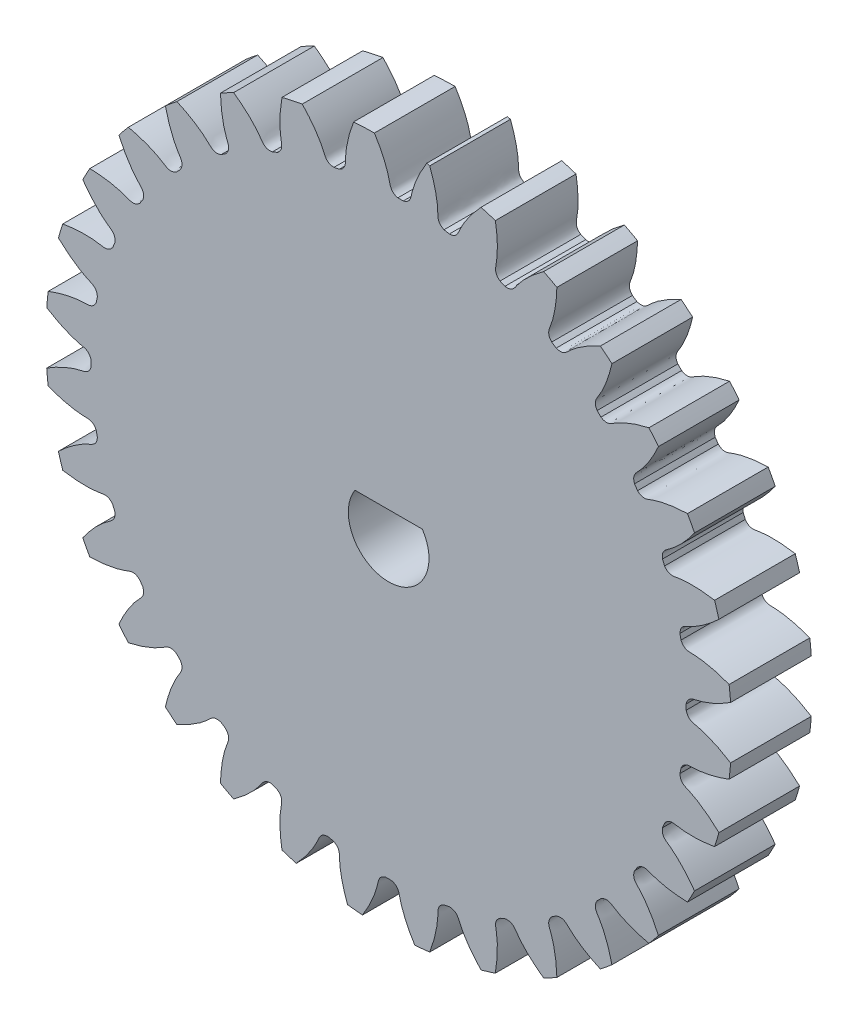
SolidWorks part; units mm, degrees
ref_plane "前视基准面" through (0, 0, 0) normal (0, 0, 1) x (1, 0, 0)
ref_plane "上视基准面" through (0, 0, 0) normal (0, 1, 0) x (1, 0, 0)
ref_plane "右视基准面" through (0, 0, 0) normal (1, 0, 0) x (0, 0, -1)
sketch "草图1" plane through (0, 0, 0) normal (0, 0, 1) x (1, 0, 0)
  line L1 (-1.6703, 1.1) -> (1.6703, 1.1)
  arc A0 (2.0353, 16.8777) -> (1.887, 16.9176) centre (-2.4495, 0.5141) ccw
  arc A1 (0.7245, 14.7165) -> (0.4565, 14.7165) centre (0.5905, -0.0328) ccw
  arc A2 (-0.706, 16.9176) -> (-1.7388, 16.8777) centre (-0.5662, -0.0818) ccw
  arc A3 (-2.4495, 14.4921) -> (-2.7124, 14.4398) centre (0.2965, 0) ccw
  arc A4 (-4.282, 16.3719) -> (-5.2889, 16.1564) centre (-1.2293, -0.3518) ccw
  arc A5 (-5.5205, 13.678) -> (-5.7682, 13.5754) centre (0, 0) ccw
  arc A6 (-7.6845, 15.1641) -> (-8.3392, 14.8141) centre (0, 0) ccw
  arc A7 (-8.0829, 12.3381) -> (-8.3058, 12.1892) centre (0, 0) ccw
  arc A8 (-10.4952, 13.3735) -> (-11.069, 12.9026) centre (0, 0) ccw
  arc A9 (-10.3346, 10.5242) -> (-10.5242, 10.3346) centre (0, 0) ccw
  arc A10 (-12.9026, 11.069) -> (-13.3735, 10.4952) centre (0, 0) ccw
  arc A11 (-12.1892, 8.3058) -> (-12.3381, 8.0829) centre (0, 0) ccw
  arc A12 (-14.8141, 8.3392) -> (-15.1641, 7.6845) centre (0, 0) ccw
  arc A13 (-13.5754, 5.7682) -> (-13.678, 5.5205) centre (0, 0) ccw
  arc A14 (-16.1564, 5.2889) -> (-16.3719, 4.5785) centre (0, 0) ccw
  arc A15 (-14.4398, 3.0089) -> (-14.4921, 2.746) centre (0, 0) ccw
  arc A16 (-16.8777, 2.0353) -> (-16.9505, 1.2965) centre (0, 0) ccw
  arc A17 (-14.7494, 0.134) -> (-14.7494, -0.134) centre (0, 0) ccw
  arc A18 (-16.9505, -1.2965) -> (-16.8777, -2.0353) centre (0, 0) ccw
  arc A19 (-14.4921, -2.746) -> (-14.4398, -3.0089) centre (0, 0) ccw
  arc A20 (-16.3719, -4.5785) -> (-16.1564, -5.2889) centre (0, 0) ccw
  arc A21 (-13.678, -5.5205) -> (-13.5754, -5.7682) centre (0, 0) ccw
  arc A22 (-15.1641, -7.6845) -> (-14.8141, -8.3392) centre (0, 0) ccw
  arc A23 (-12.3381, -8.0829) -> (-12.1892, -8.3058) centre (0, 0) ccw
  arc A24 (-13.3735, -10.4952) -> (-12.9026, -11.069) centre (0, 0) ccw
  arc A25 (-10.5242, -10.3346) -> (-10.3346, -10.5242) centre (0, 0) ccw
  arc A26 (-11.069, -12.9026) -> (-10.4952, -13.3735) centre (0, 0) ccw
  arc A27 (-8.3058, -12.1892) -> (-8.0829, -12.3381) centre (0, 0) ccw
  arc A28 (-8.3392, -14.8141) -> (-7.6845, -15.1641) centre (0, 0) ccw
  arc A29 (-5.7682, -13.5754) -> (-5.5205, -13.678) centre (0, 0) ccw
  arc A30 (-5.2889, -16.1564) -> (-4.5785, -16.3719) centre (0, 0) ccw
  arc A31 (-3.0089, -14.4398) -> (-2.746, -14.4921) centre (0, 0) ccw
  arc A32 (-2.0353, -16.8777) -> (-1.2965, -16.9505) centre (0, 0) ccw
  arc A33 (-0.134, -14.7494) -> (0.134, -14.7494) centre (0, 0) ccw
  arc A34 (1.2965, -16.9505) -> (2.0353, -16.8777) centre (0, 0) ccw
  arc A35 (2.746, -14.4921) -> (3.0089, -14.4398) centre (0, 0) ccw
  arc A36 (4.5785, -16.3719) -> (5.2889, -16.1564) centre (0, 0) ccw
  arc A37 (5.5205, -13.678) -> (5.7682, -13.5754) centre (0, 0) ccw
  arc A38 (7.6845, -15.1641) -> (8.3392, -14.8141) centre (0, 0) ccw
  arc A39 (8.0829, -12.3381) -> (8.3058, -12.1892) centre (0, 0) ccw
  arc A40 (10.4952, -13.3735) -> (11.069, -12.9026) centre (0, 0) ccw
  arc A41 (10.3346, -10.5242) -> (10.5242, -10.3346) centre (0, 0) ccw
  arc A42 (12.9026, -11.069) -> (13.3735, -10.4952) centre (0, 0) ccw
  arc A43 (12.1892, -8.3058) -> (12.3381, -8.0829) centre (0, 0) ccw
  arc A44 (14.8141, -8.3392) -> (15.1641, -7.6845) centre (0, 0) ccw
  arc A45 (13.5754, -5.7682) -> (13.678, -5.5205) centre (0, 0) ccw
  arc A46 (16.1564, -5.2889) -> (16.3719, -4.5785) centre (0, 0) ccw
  arc A47 (14.4398, -3.0089) -> (14.4921, -2.746) centre (0, 0) ccw
  arc A48 (16.8777, -2.0353) -> (16.9505, -1.2965) centre (0, 0) ccw
  arc A49 (14.7494, -0.134) -> (14.7494, 0.134) centre (0, 0) ccw
  arc A50 (16.9505, 1.2965) -> (16.8777, 2.0353) centre (0, 0) ccw
  arc A51 (14.4921, 2.746) -> (14.4398, 3.0089) centre (0, 0) ccw
  arc A52 (16.3719, 4.5785) -> (16.1564, 5.2889) centre (0, 0) ccw
  arc A53 (13.678, 5.5205) -> (13.5754, 5.7682) centre (0, 0) ccw
  arc A54 (15.1641, 7.6845) -> (14.8141, 8.3392) centre (0, 0) ccw
  arc A55 (12.3381, 8.0829) -> (12.1892, 8.3058) centre (0, 0) ccw
  arc A56 (13.3735, 10.4952) -> (12.9026, 11.069) centre (0, 0) ccw
  arc A57 (10.5242, 10.3346) -> (10.3346, 10.5242) centre (0, 0) ccw
  arc A58 (11.069, 12.9026) -> (10.4952, 13.3735) centre (0, 0) ccw
  arc A59 (8.3058, 12.1892) -> (8.0829, 12.3381) centre (0, 0) ccw
  arc A60 (8.3392, 14.8141) -> (7.6845, 15.1641) centre (0, 0) ccw
  arc A61 (5.7682, 13.5754) -> (5.5205, 13.678) centre (0, 0) ccw
  arc A62 (5.2889, 16.1564) -> (4.5785, 16.3719) centre (0, 0) ccw
  arc A63 (3.0089, 14.4398) -> (2.746, 14.4921) centre (0, 0) ccw
  arc A65 (-1.6703, 1.1) -> (1.6703, 1.1) centre (0, 0) ccw
  spline S0 degree 3 poles (1.887, 16.9176) (1.8385, 16.8406) (1.7423, 16.6818) (1.61, 16.4438) (1.493, 16.2117) (1.3953, 15.9971) (1.3153, 15.801) (1.2513, 15.6245) (1.2085, 15.4897) (1.1809, 15.3925) (1.1639, 15.3279) (1.0989, 15.0596) (1.0793, 14.8023) (0.7245, 14.7165) knots 0 0 0 0 0.048515 0.098957 0.145126 0.18702 0.22464 0.257986 0.287058 0.299991 0.311856 0.322652 0.447185 0.447185 0.447185 0.447185
  spline S1 degree 3 poles (0.4565, 14.7165) (0.1017, 14.8023) (0.0821, 15.0596) (0.0171, 15.3279) (0.0001, 15.3925) (-0.0275, 15.4897) (-0.0703, 15.6245) (-0.1342, 15.801) (-0.2142, 15.9971) (-0.312, 16.2117) (-0.429, 16.4438) (-0.5613, 16.6818) (-0.6575, 16.8406) (-0.706, 16.9176) knots 0 0 0 0 0.124533 0.135329 0.147193 0.160126 0.189198 0.222544 0.260164 0.302059 0.348227 0.39867 0.447185 0.447185 0.447185 0.447185
  spline S2 degree 3 poles (-1.7388, 16.8777) (-1.7713, 16.7927) (-1.8347, 16.6182) (-1.918, 16.3589) (-1.9875, 16.1085) (-2.0415, 15.8789) (-2.0817, 15.671) (-2.11, 15.4854) (-2.1257, 15.3449) (-2.1338, 15.2441) (-2.1378, 15.1775) (-2.1493, 14.9016) (-2.1183, 14.6455) (-2.4495, 14.4921) knots 0 0 0 0 0.048515 0.098957 0.145126 0.18702 0.22464 0.257986 0.287058 0.299991 0.311856 0.322652 0.447185 0.447185 0.447185 0.447185
  spline S3 degree 3 poles (-2.7124, 14.4398) (-3.0771, 14.4548) (-3.1465, 14.7032) (-3.2626, 14.9537) (-3.2919, 15.0138) (-3.3379, 15.1038) (-3.4062, 15.2276) (-3.5033, 15.3882) (-3.6201, 15.5649) (-3.7578, 15.7564) (-3.9179, 15.9611) (-4.094, 16.1688) (-4.2194, 16.3058) (-4.282, 16.3719) knots 0 0 0 0 0.124533 0.135329 0.147193 0.160126 0.189198 0.222544 0.260164 0.302059 0.348227 0.39867 0.447185 0.447185 0.447185 0.447185
  spline S4 degree 3 poles (-5.2889, 16.1564) (-5.3042, 16.0666) (-5.3323, 15.8831) (-5.3634, 15.6126) (-5.3827, 15.3534) (-5.3909, 15.1177) (-5.3898, 14.9059) (-5.3813, 14.7184) (-5.3693, 14.5775) (-5.3576, 14.4771) (-5.3485, 14.4109) (-5.3059, 14.1381) (-5.2256, 13.893) (-5.5205, 13.678) knots 0 0 0 0 0.048515 0.098957 0.145126 0.18702 0.22464 0.257986 0.287058 0.299991 0.311856 0.322652 0.447185 0.447185 0.447185 0.447185
  spline S5 degree 3 poles (-5.7682, 13.5754) (-6.1288, 13.5188) (-6.2453, 13.749) (-6.4081, 13.9721) (-6.4485, 14.0253) (-6.5112, 14.1045) (-6.6023, 14.2126) (-6.7289, 14.3512) (-6.8779, 14.5017) (-7.0503, 14.6626) (-7.2473, 14.8322) (-7.4605, 15.0016) (-7.6102, 15.1115) (-7.6845, 15.1641) knots 0 0 0 0 0.124533 0.135329 0.147193 0.160126 0.189198 0.222544 0.260164 0.302059 0.348227 0.39867 0.447185 0.447185 0.447185 0.447185
  spline S6 degree 3 poles (-8.3392, 14.8141) (-8.3367, 14.7231) (-8.3285, 14.5376) (-8.3062, 14.2662) (-8.2746, 14.0082) (-8.2366, 13.7755) (-8.1942, 13.568) (-8.1493, 13.3857) (-8.1101, 13.2499) (-8.079, 13.1537) (-8.0572, 13.0906) (-7.9622, 12.8313) (-7.8355, 12.6066) (-8.0829, 12.3381) knots 0 0 0 0 0.048515 0.098957 0.145126 0.18702 0.22464 0.257986 0.287058 0.299991 0.311856 0.322652 0.447185 0.447185 0.447185 0.447185
  spline S7 degree 3 poles (-8.3058, 12.1892) (-8.6484, 12.0634) (-8.8076, 12.2664) (-9.0108, 12.4534) (-9.0607, 12.4977) (-9.1377, 12.5632) (-9.2482, 12.6515) (-9.3994, 12.7627) (-9.5749, 12.8813) (-9.7754, 13.0055) (-10.0016, 13.1334) (-10.2439, 13.2578) (-10.4121, 13.3364) (-10.4952, 13.3735) knots 0 0 0 0 0.124533 0.135329 0.147193 0.160126 0.189198 0.222544 0.260164 0.302059 0.348227 0.39867 0.447185 0.447185 0.447185 0.447185
  spline S8 degree 3 poles (-11.069, 12.9026) (-11.0489, 12.8138) (-11.0046, 12.6335) (-10.9298, 12.3716) (-10.8485, 12.1248) (-10.7658, 11.9039) (-10.6837, 11.7087) (-10.6041, 11.5387) (-10.5391, 11.4131) (-10.4899, 11.3248) (-10.4562, 11.2672) (-10.3125, 11.0314) (-10.1444, 10.8357) (-10.3346, 10.5242) knots 0 0 0 0 0.048515 0.098957 0.145126 0.18702 0.22464 0.257986 0.287058 0.299991 0.311856 0.322652 0.447185 0.447185 0.447185 0.447185
  spline S9 degree 3 poles (-10.5242, 10.3346) (-10.8357, 10.1444) (-11.0314, 10.3125) (-11.2672, 10.4562) (-11.3248, 10.4899) (-11.4131, 10.5391) (-11.5387, 10.6041) (-11.7087, 10.6837) (-11.9039, 10.7658) (-12.1248, 10.8485) (-12.3716, 10.9298) (-12.6335, 11.0046) (-12.8138, 11.0489) (-12.9026, 11.069) knots 0 0 0 0 0.124533 0.135329 0.147193 0.160126 0.189198 0.222544 0.260164 0.302059 0.348227 0.39867 0.447185 0.447185 0.447185 0.447185
  spline S10 degree 3 poles (-13.3735, 10.4952) (-13.3364, 10.4121) (-13.2578, 10.2439) (-13.1334, 10.0016) (-13.0055, 9.7754) (-12.8813, 9.5749) (-12.7627, 9.3994) (-12.6515, 9.2482) (-12.5632, 9.1377) (-12.4977, 9.0607) (-12.4534, 9.0108) (-12.2664, 8.8076) (-12.0634, 8.6484) (-12.1892, 8.3058) knots 0 0 0 0 0.048515 0.098957 0.145126 0.18702 0.22464 0.257986 0.287058 0.299991 0.311856 0.322652 0.447185 0.447185 0.447185 0.447185
  spline S11 degree 3 poles (-12.3381, 8.0829) (-12.6066, 7.8355) (-12.8313, 7.9622) (-13.0906, 8.0572) (-13.1537, 8.079) (-13.2499, 8.1101) (-13.3857, 8.1493) (-13.568, 8.1942) (-13.7755, 8.2366) (-14.0082, 8.2746) (-14.2662, 8.3062) (-14.5376, 8.3285) (-14.7231, 8.3367) (-14.8141, 8.3392) knots 0 0 0 0 0.124533 0.135329 0.147193 0.160126 0.189198 0.222544 0.260164 0.302059 0.348227 0.39867 0.447185 0.447185 0.447185 0.447185
  spline S12 degree 3 poles (-15.1641, 7.6845) (-15.1115, 7.6102) (-15.0016, 7.4605) (-14.8322, 7.2473) (-14.6626, 7.0503) (-14.5017, 6.8779) (-14.3512, 6.7289) (-14.2126, 6.6023) (-14.1045, 6.5112) (-14.0253, 6.4485) (-13.9721, 6.4081) (-13.749, 6.2453) (-13.5188, 6.1288) (-13.5754, 5.7682) knots 0 0 0 0 0.048515 0.098957 0.145126 0.18702 0.22464 0.257986 0.287058 0.299991 0.311856 0.322652 0.447185 0.447185 0.447185 0.447185
  spline S13 degree 3 poles (-13.678, 5.5205) (-13.893, 5.2256) (-14.1381, 5.3059) (-14.4109, 5.3485) (-14.4771, 5.3576) (-14.5775, 5.3693) (-14.7184, 5.3813) (-14.9059, 5.3898) (-15.1177, 5.3909) (-15.3534, 5.3827) (-15.6126, 5.3634) (-15.8831, 5.3323) (-16.0666, 5.3042) (-16.1564, 5.2889) knots 0 0 0 0 0.124533 0.135329 0.147193 0.160126 0.189198 0.222544 0.260164 0.302059 0.348227 0.39867 0.447185 0.447185 0.447185 0.447185
  spline S14 degree 3 poles (-16.3719, 4.5785) (-16.3058, 4.5159) (-16.1688, 4.3905) (-15.9611, 4.2144) (-15.7564, 4.0543) (-15.5649, 3.9166) (-15.3882, 3.7998) (-15.2276, 3.7027) (-15.1038, 3.6344) (-15.0138, 3.5884) (-14.9537, 3.5591) (-14.7032, 3.443) (-14.4548, 3.3736) (-14.4398, 3.0089) knots 0 0 0 0 0.048515 0.098957 0.145126 0.18702 0.22464 0.257986 0.287058 0.299991 0.311856 0.322652 0.447185 0.447185 0.447185 0.447185
  spline S15 degree 3 poles (-14.4921, 2.746) (-14.6455, 2.4148) (-14.9016, 2.4458) (-15.1775, 2.4343) (-15.2441, 2.4303) (-15.3449, 2.4222) (-15.4854, 2.4065) (-15.671, 2.3782) (-15.8789, 2.338) (-16.1085, 2.284) (-16.3589, 2.2145) (-16.6182, 2.1312) (-16.7927, 2.0678) (-16.8777, 2.0353) knots 0 0 0 0 0.124533 0.135329 0.147193 0.160126 0.189198 0.222544 0.260164 0.302059 0.348227 0.39867 0.447185 0.447185 0.447185 0.447185
  spline S16 degree 3 poles (-16.9505, 1.2965) (-16.8735, 1.248) (-16.7147, 1.1518) (-16.4766, 1.0195) (-16.2446, 0.9025) (-16.0299, 0.8048) (-15.8338, 0.7247) (-15.6573, 0.6608) (-15.5226, 0.618) (-15.4254, 0.5904) (-15.3608, 0.5734) (-15.0924, 0.5084) (-14.8352, 0.4888) (-14.7494, 0.134) knots 0 0 0 0 0.048515 0.098957 0.145126 0.18702 0.22464 0.257986 0.287058 0.299991 0.311856 0.322652 0.447185 0.447185 0.447185 0.447185
  spline S17 degree 3 poles (-14.7494, -0.134) (-14.8352, -0.4888) (-15.0924, -0.5084) (-15.3608, -0.5734) (-15.4254, -0.5904) (-15.5226, -0.618) (-15.6573, -0.6608) (-15.8338, -0.7247) (-16.0299, -0.8048) (-16.2446, -0.9025) (-16.4766, -1.0195) (-16.7147, -1.1518) (-16.8735, -1.248) (-16.9505, -1.2965) knots 0 0 0 0 0.124533 0.135329 0.147193 0.160126 0.189198 0.222544 0.260164 0.302059 0.348227 0.39867 0.447185 0.447185 0.447185 0.447185
  spline S18 degree 3 poles (-16.8777, -2.0353) (-16.7927, -2.0678) (-16.6182, -2.1312) (-16.3589, -2.2145) (-16.1085, -2.284) (-15.8789, -2.338) (-15.671, -2.3782) (-15.4854, -2.4065) (-15.3449, -2.4222) (-15.2441, -2.4303) (-15.1775, -2.4343) (-14.9016, -2.4458) (-14.6455, -2.4148) (-14.4921, -2.746) knots 0 0 0 0 0.048515 0.098957 0.145126 0.18702 0.22464 0.257986 0.287058 0.299991 0.311856 0.322652 0.447185 0.447185 0.447185 0.447185
  spline S19 degree 3 poles (-14.4398, -3.0089) (-14.4548, -3.3736) (-14.7032, -3.443) (-14.9537, -3.5591) (-15.0138, -3.5884) (-15.1038, -3.6344) (-15.2276, -3.7027) (-15.3882, -3.7998) (-15.5649, -3.9166) (-15.7564, -4.0543) (-15.9611, -4.2144) (-16.1688, -4.3905) (-16.3058, -4.5159) (-16.3719, -4.5785) knots 0 0 0 0 0.124533 0.135329 0.147193 0.160126 0.189198 0.222544 0.260164 0.302059 0.348227 0.39867 0.447185 0.447185 0.447185 0.447185
  spline S20 degree 3 poles (-16.1564, -5.2889) (-16.0666, -5.3042) (-15.8831, -5.3323) (-15.6126, -5.3634) (-15.3534, -5.3827) (-15.1177, -5.3909) (-14.9059, -5.3898) (-14.7184, -5.3813) (-14.5775, -5.3693) (-14.4771, -5.3576) (-14.4109, -5.3485) (-14.1381, -5.3059) (-13.893, -5.2256) (-13.678, -5.5205) knots 0 0 0 0 0.048515 0.098957 0.145126 0.18702 0.22464 0.257986 0.287058 0.299991 0.311856 0.322652 0.447185 0.447185 0.447185 0.447185
  spline S21 degree 3 poles (-13.5754, -5.7682) (-13.5188, -6.1288) (-13.749, -6.2453) (-13.9721, -6.4081) (-14.0253, -6.4485) (-14.1045, -6.5112) (-14.2126, -6.6023) (-14.3512, -6.7289) (-14.5017, -6.8779) (-14.6626, -7.0503) (-14.8322, -7.2473) (-15.0016, -7.4605) (-15.1115, -7.6102) (-15.1641, -7.6845) knots 0 0 0 0 0.124533 0.135329 0.147193 0.160126 0.189198 0.222544 0.260164 0.302059 0.348227 0.39867 0.447185 0.447185 0.447185 0.447185
  spline S22 degree 3 poles (-14.8141, -8.3392) (-14.7231, -8.3367) (-14.5376, -8.3285) (-14.2662, -8.3062) (-14.0082, -8.2746) (-13.7755, -8.2366) (-13.568, -8.1942) (-13.3857, -8.1493) (-13.2499, -8.1101) (-13.1537, -8.079) (-13.0906, -8.0572) (-12.8313, -7.9622) (-12.6066, -7.8355) (-12.3381, -8.0829) knots 0 0 0 0 0.048515 0.098957 0.145126 0.18702 0.22464 0.257986 0.287058 0.299991 0.311856 0.322652 0.447185 0.447185 0.447185 0.447185
  spline S23 degree 3 poles (-12.1892, -8.3058) (-12.0634, -8.6484) (-12.2664, -8.8076) (-12.4534, -9.0108) (-12.4977, -9.0607) (-12.5632, -9.1377) (-12.6515, -9.2482) (-12.7627, -9.3994) (-12.8813, -9.5749) (-13.0055, -9.7754) (-13.1334, -10.0016) (-13.2578, -10.2439) (-13.3364, -10.4121) (-13.3735, -10.4952) knots 0 0 0 0 0.124533 0.135329 0.147193 0.160126 0.189198 0.222544 0.260164 0.302059 0.348227 0.39867 0.447185 0.447185 0.447185 0.447185
  spline S24 degree 3 poles (-12.9026, -11.069) (-12.8138, -11.0489) (-12.6335, -11.0046) (-12.3716, -10.9298) (-12.1248, -10.8485) (-11.9039, -10.7658) (-11.7087, -10.6837) (-11.5387, -10.6041) (-11.4131, -10.5391) (-11.3248, -10.4899) (-11.2672, -10.4562) (-11.0314, -10.3125) (-10.8357, -10.1444) (-10.5242, -10.3346) knots 0 0 0 0 0.048515 0.098957 0.145126 0.18702 0.22464 0.257986 0.287058 0.299991 0.311856 0.322652 0.447185 0.447185 0.447185 0.447185
  spline S25 degree 3 poles (-10.3346, -10.5242) (-10.1444, -10.8357) (-10.3125, -11.0314) (-10.4562, -11.2672) (-10.4899, -11.3248) (-10.5391, -11.4131) (-10.6041, -11.5387) (-10.6837, -11.7087) (-10.7658, -11.9039) (-10.8485, -12.1248) (-10.9298, -12.3716) (-11.0046, -12.6335) (-11.0489, -12.8138) (-11.069, -12.9026) knots 0 0 0 0 0.124533 0.135329 0.147193 0.160126 0.189198 0.222544 0.260164 0.302059 0.348227 0.39867 0.447185 0.447185 0.447185 0.447185
  spline S26 degree 3 poles (-10.4952, -13.3735) (-10.4121, -13.3364) (-10.2439, -13.2578) (-10.0016, -13.1334) (-9.7754, -13.0055) (-9.5749, -12.8813) (-9.3994, -12.7627) (-9.2482, -12.6515) (-9.1377, -12.5632) (-9.0607, -12.4977) (-9.0108, -12.4534) (-8.8076, -12.2664) (-8.6484, -12.0634) (-8.3058, -12.1892) knots 0 0 0 0 0.048515 0.098957 0.145126 0.18702 0.22464 0.257986 0.287058 0.299991 0.311856 0.322652 0.447185 0.447185 0.447185 0.447185
  spline S27 degree 3 poles (-8.0829, -12.3381) (-7.8355, -12.6066) (-7.9622, -12.8313) (-8.0572, -13.0906) (-8.079, -13.1537) (-8.1101, -13.2499) (-8.1493, -13.3857) (-8.1942, -13.568) (-8.2366, -13.7755) (-8.2746, -14.0082) (-8.3062, -14.2662) (-8.3285, -14.5376) (-8.3367, -14.7231) (-8.3392, -14.8141) knots 0 0 0 0 0.124533 0.135329 0.147193 0.160126 0.189198 0.222544 0.260164 0.302059 0.348227 0.39867 0.447185 0.447185 0.447185 0.447185
  spline S28 degree 3 poles (-7.6845, -15.1641) (-7.6102, -15.1115) (-7.4605, -15.0016) (-7.2473, -14.8322) (-7.0503, -14.6626) (-6.8779, -14.5017) (-6.7289, -14.3512) (-6.6023, -14.2126) (-6.5112, -14.1045) (-6.4485, -14.0253) (-6.4081, -13.9721) (-6.2453, -13.749) (-6.1288, -13.5188) (-5.7682, -13.5754) knots 0 0 0 0 0.048515 0.098957 0.145126 0.18702 0.22464 0.257986 0.287058 0.299991 0.311856 0.322652 0.447185 0.447185 0.447185 0.447185
  spline S29 degree 3 poles (-5.5205, -13.678) (-5.2256, -13.893) (-5.3059, -14.1381) (-5.3485, -14.4109) (-5.3576, -14.4771) (-5.3693, -14.5775) (-5.3813, -14.7184) (-5.3898, -14.9059) (-5.3909, -15.1177) (-5.3827, -15.3534) (-5.3634, -15.6126) (-5.3323, -15.8831) (-5.3042, -16.0666) (-5.2889, -16.1564) knots 0 0 0 0 0.124533 0.135329 0.147193 0.160126 0.189198 0.222544 0.260164 0.302059 0.348227 0.39867 0.447185 0.447185 0.447185 0.447185
  spline S30 degree 3 poles (-4.5785, -16.3719) (-4.5159, -16.3058) (-4.3905, -16.1688) (-4.2144, -15.9611) (-4.0543, -15.7564) (-3.9166, -15.5649) (-3.7998, -15.3882) (-3.7027, -15.2276) (-3.6344, -15.1038) (-3.5884, -15.0138) (-3.5591, -14.9537) (-3.443, -14.7032) (-3.3736, -14.4548) (-3.0089, -14.4398) knots 0 0 0 0 0.048515 0.098957 0.145126 0.18702 0.22464 0.257986 0.287058 0.299991 0.311856 0.322652 0.447185 0.447185 0.447185 0.447185
  spline S31 degree 3 poles (-2.746, -14.4921) (-2.4148, -14.6455) (-2.4458, -14.9016) (-2.4343, -15.1775) (-2.4303, -15.2441) (-2.4222, -15.3449) (-2.4065, -15.4854) (-2.3782, -15.671) (-2.338, -15.8789) (-2.284, -16.1085) (-2.2145, -16.3589) (-2.1312, -16.6182) (-2.0678, -16.7927) (-2.0353, -16.8777) knots 0 0 0 0 0.124533 0.135329 0.147193 0.160126 0.189198 0.222544 0.260164 0.302059 0.348227 0.39867 0.447185 0.447185 0.447185 0.447185
  spline S32 degree 3 poles (-1.2965, -16.9505) (-1.248, -16.8735) (-1.1518, -16.7147) (-1.0195, -16.4766) (-0.9025, -16.2446) (-0.8048, -16.0299) (-0.7247, -15.8338) (-0.6608, -15.6573) (-0.618, -15.5226) (-0.5904, -15.4254) (-0.5734, -15.3608) (-0.5084, -15.0924) (-0.4888, -14.8352) (-0.134, -14.7494) knots 0 0 0 0 0.048515 0.098957 0.145126 0.18702 0.22464 0.257986 0.287058 0.299991 0.311856 0.322652 0.447185 0.447185 0.447185 0.447185
  spline S33 degree 3 poles (0.134, -14.7494) (0.4888, -14.8352) (0.5084, -15.0924) (0.5734, -15.3608) (0.5904, -15.4254) (0.618, -15.5226) (0.6608, -15.6573) (0.7247, -15.8338) (0.8048, -16.0299) (0.9025, -16.2446) (1.0195, -16.4766) (1.1518, -16.7147) (1.248, -16.8735) (1.2965, -16.9505) knots 0 0 0 0 0.124533 0.135329 0.147193 0.160126 0.189198 0.222544 0.260164 0.302059 0.348227 0.39867 0.447185 0.447185 0.447185 0.447185
  spline S34 degree 3 poles (2.0353, -16.8777) (2.0678, -16.7927) (2.1312, -16.6182) (2.2145, -16.3589) (2.284, -16.1085) (2.338, -15.8789) (2.3782, -15.671) (2.4065, -15.4854) (2.4222, -15.3449) (2.4303, -15.2441) (2.4343, -15.1775) (2.4458, -14.9016) (2.4148, -14.6455) (2.746, -14.4921) knots 0 0 0 0 0.048515 0.098957 0.145126 0.18702 0.22464 0.257986 0.287058 0.299991 0.311856 0.322652 0.447185 0.447185 0.447185 0.447185
  spline S35 degree 3 poles (3.0089, -14.4398) (3.3736, -14.4548) (3.443, -14.7032) (3.5591, -14.9537) (3.5884, -15.0138) (3.6344, -15.1038) (3.7027, -15.2276) (3.7998, -15.3882) (3.9166, -15.5649) (4.0543, -15.7564) (4.2144, -15.9611) (4.3905, -16.1688) (4.5159, -16.3058) (4.5785, -16.3719) knots 0 0 0 0 0.124533 0.135329 0.147193 0.160126 0.189198 0.222544 0.260164 0.302059 0.348227 0.39867 0.447185 0.447185 0.447185 0.447185
  spline S36 degree 3 poles (5.2889, -16.1564) (5.3042, -16.0666) (5.3323, -15.8831) (5.3634, -15.6126) (5.3827, -15.3534) (5.3909, -15.1177) (5.3898, -14.9059) (5.3813, -14.7184) (5.3693, -14.5775) (5.3576, -14.4771) (5.3485, -14.4109) (5.3059, -14.1381) (5.2256, -13.893) (5.5205, -13.678) knots 0 0 0 0 0.048515 0.098957 0.145126 0.18702 0.22464 0.257986 0.287058 0.299991 0.311856 0.322652 0.447185 0.447185 0.447185 0.447185
  spline S37 degree 3 poles (5.7682, -13.5754) (6.1288, -13.5188) (6.2453, -13.749) (6.4081, -13.9721) (6.4485, -14.0253) (6.5112, -14.1045) (6.6023, -14.2126) (6.7289, -14.3512) (6.8779, -14.5017) (7.0503, -14.6626) (7.2473, -14.8322) (7.4605, -15.0016) (7.6102, -15.1115) (7.6845, -15.1641) knots 0 0 0 0 0.124533 0.135329 0.147193 0.160126 0.189198 0.222544 0.260164 0.302059 0.348227 0.39867 0.447185 0.447185 0.447185 0.447185
  spline S38 degree 3 poles (8.3392, -14.8141) (8.3367, -14.7231) (8.3285, -14.5376) (8.3062, -14.2662) (8.2746, -14.0082) (8.2366, -13.7755) (8.1942, -13.568) (8.1493, -13.3857) (8.1101, -13.2499) (8.079, -13.1537) (8.0572, -13.0906) (7.9622, -12.8313) (7.8355, -12.6066) (8.0829, -12.3381) knots 0 0 0 0 0.048515 0.098957 0.145126 0.18702 0.22464 0.257986 0.287058 0.299991 0.311856 0.322652 0.447185 0.447185 0.447185 0.447185
  spline S39 degree 3 poles (8.3058, -12.1892) (8.6484, -12.0634) (8.8076, -12.2664) (9.0108, -12.4534) (9.0607, -12.4977) (9.1377, -12.5632) (9.2482, -12.6515) (9.3994, -12.7627) (9.5749, -12.8813) (9.7754, -13.0055) (10.0016, -13.1334) (10.2439, -13.2578) (10.4121, -13.3364) (10.4952, -13.3735) knots 0 0 0 0 0.124533 0.135329 0.147193 0.160126 0.189198 0.222544 0.260164 0.302059 0.348227 0.39867 0.447185 0.447185 0.447185 0.447185
  spline S40 degree 3 poles (11.069, -12.9026) (11.0489, -12.8138) (11.0046, -12.6335) (10.9298, -12.3716) (10.8485, -12.1248) (10.7658, -11.9039) (10.6837, -11.7087) (10.6041, -11.5387) (10.5391, -11.4131) (10.4899, -11.3248) (10.4562, -11.2672) (10.3125, -11.0314) (10.1444, -10.8357) (10.3346, -10.5242) knots 0 0 0 0 0.048515 0.098957 0.145126 0.18702 0.22464 0.257986 0.287058 0.299991 0.311856 0.322652 0.447185 0.447185 0.447185 0.447185
  spline S41 degree 3 poles (10.5242, -10.3346) (10.8357, -10.1444) (11.0314, -10.3125) (11.2672, -10.4562) (11.3248, -10.4899) (11.4131, -10.5391) (11.5387, -10.6041) (11.7087, -10.6837) (11.9039, -10.7658) (12.1248, -10.8485) (12.3716, -10.9298) (12.6335, -11.0046) (12.8138, -11.0489) (12.9026, -11.069) knots 0 0 0 0 0.124533 0.135329 0.147193 0.160126 0.189198 0.222544 0.260164 0.302059 0.348227 0.39867 0.447185 0.447185 0.447185 0.447185
  spline S42 degree 3 poles (13.3735, -10.4952) (13.3364, -10.4121) (13.2578, -10.2439) (13.1334, -10.0016) (13.0055, -9.7754) (12.8813, -9.5749) (12.7627, -9.3994) (12.6515, -9.2482) (12.5632, -9.1377) (12.4977, -9.0607) (12.4534, -9.0108) (12.2664, -8.8076) (12.0634, -8.6484) (12.1892, -8.3058) knots 0 0 0 0 0.048515 0.098957 0.145126 0.18702 0.22464 0.257986 0.287058 0.299991 0.311856 0.322652 0.447185 0.447185 0.447185 0.447185
  spline S43 degree 3 poles (12.3381, -8.0829) (12.6066, -7.8355) (12.8313, -7.9622) (13.0906, -8.0572) (13.1537, -8.079) (13.2499, -8.1101) (13.3857, -8.1493) (13.568, -8.1942) (13.7755, -8.2366) (14.0082, -8.2746) (14.2662, -8.3062) (14.5376, -8.3285) (14.7231, -8.3367) (14.8141, -8.3392) knots 0 0 0 0 0.124533 0.135329 0.147193 0.160126 0.189198 0.222544 0.260164 0.302059 0.348227 0.39867 0.447185 0.447185 0.447185 0.447185
  spline S44 degree 3 poles (15.1641, -7.6845) (15.1115, -7.6102) (15.0016, -7.4605) (14.8322, -7.2473) (14.6626, -7.0503) (14.5017, -6.8779) (14.3512, -6.7289) (14.2126, -6.6023) (14.1045, -6.5112) (14.0253, -6.4485) (13.9721, -6.4081) (13.749, -6.2453) (13.5188, -6.1288) (13.5754, -5.7682) knots 0 0 0 0 0.048515 0.098957 0.145126 0.18702 0.22464 0.257986 0.287058 0.299991 0.311856 0.322652 0.447185 0.447185 0.447185 0.447185
  spline S45 degree 3 poles (13.678, -5.5205) (13.893, -5.2256) (14.1381, -5.3059) (14.4109, -5.3485) (14.4771, -5.3576) (14.5775, -5.3693) (14.7184, -5.3813) (14.9059, -5.3898) (15.1177, -5.3909) (15.3534, -5.3827) (15.6126, -5.3634) (15.8831, -5.3323) (16.0666, -5.3042) (16.1564, -5.2889) knots 0 0 0 0 0.124533 0.135329 0.147193 0.160126 0.189198 0.222544 0.260164 0.302059 0.348227 0.39867 0.447185 0.447185 0.447185 0.447185
  spline S46 degree 3 poles (16.3719, -4.5785) (16.3058, -4.5159) (16.1688, -4.3905) (15.9611, -4.2144) (15.7564, -4.0543) (15.5649, -3.9166) (15.3882, -3.7998) (15.2276, -3.7027) (15.1038, -3.6344) (15.0138, -3.5884) (14.9537, -3.5591) (14.7032, -3.443) (14.4548, -3.3736) (14.4398, -3.0089) knots 0 0 0 0 0.048515 0.098957 0.145126 0.18702 0.22464 0.257986 0.287058 0.299991 0.311856 0.322652 0.447185 0.447185 0.447185 0.447185
  spline S47 degree 3 poles (14.4921, -2.746) (14.6455, -2.4148) (14.9016, -2.4458) (15.1775, -2.4343) (15.2441, -2.4303) (15.3449, -2.4222) (15.4854, -2.4065) (15.671, -2.3782) (15.8789, -2.338) (16.1085, -2.284) (16.3589, -2.2145) (16.6182, -2.1312) (16.7927, -2.0678) (16.8777, -2.0353) knots 0 0 0 0 0.124533 0.135329 0.147193 0.160126 0.189198 0.222544 0.260164 0.302059 0.348227 0.39867 0.447185 0.447185 0.447185 0.447185
  spline S48 degree 3 poles (16.9505, -1.2965) (16.8735, -1.248) (16.7147, -1.1518) (16.4766, -1.0195) (16.2446, -0.9025) (16.0299, -0.8048) (15.8338, -0.7247) (15.6573, -0.6608) (15.5226, -0.618) (15.4254, -0.5904) (15.3608, -0.5734) (15.0924, -0.5084) (14.8352, -0.4888) (14.7494, -0.134) knots 0 0 0 0 0.048515 0.098957 0.145126 0.18702 0.22464 0.257986 0.287058 0.299991 0.311856 0.322652 0.447185 0.447185 0.447185 0.447185
  spline S49 degree 3 poles (14.7494, 0.134) (14.8352, 0.4888) (15.0924, 0.5084) (15.3608, 0.5734) (15.4254, 0.5904) (15.5226, 0.618) (15.6573, 0.6608) (15.8338, 0.7247) (16.0299, 0.8048) (16.2446, 0.9025) (16.4766, 1.0195) (16.7147, 1.1518) (16.8735, 1.248) (16.9505, 1.2965) knots 0 0 0 0 0.124533 0.135329 0.147193 0.160126 0.189198 0.222544 0.260164 0.302059 0.348227 0.39867 0.447185 0.447185 0.447185 0.447185
  spline S50 degree 3 poles (16.8777, 2.0353) (16.7927, 2.0678) (16.6182, 2.1312) (16.3589, 2.2145) (16.1085, 2.284) (15.8789, 2.338) (15.671, 2.3782) (15.4854, 2.4065) (15.3449, 2.4222) (15.2441, 2.4303) (15.1775, 2.4343) (14.9016, 2.4458) (14.6455, 2.4148) (14.4921, 2.746) knots 0 0 0 0 0.048515 0.098957 0.145126 0.18702 0.22464 0.257986 0.287058 0.299991 0.311856 0.322652 0.447185 0.447185 0.447185 0.447185
  spline S51 degree 3 poles (14.4398, 3.0089) (14.4548, 3.3736) (14.7032, 3.443) (14.9537, 3.5591) (15.0138, 3.5884) (15.1038, 3.6344) (15.2276, 3.7027) (15.3882, 3.7998) (15.5649, 3.9166) (15.7564, 4.0543) (15.9611, 4.2144) (16.1688, 4.3905) (16.3058, 4.5159) (16.3719, 4.5785) knots 0 0 0 0 0.124533 0.135329 0.147193 0.160126 0.189198 0.222544 0.260164 0.302059 0.348227 0.39867 0.447185 0.447185 0.447185 0.447185
  spline S52 degree 3 poles (16.1564, 5.2889) (16.0666, 5.3042) (15.8831, 5.3323) (15.6126, 5.3634) (15.3534, 5.3827) (15.1177, 5.3909) (14.9059, 5.3898) (14.7184, 5.3813) (14.5775, 5.3693) (14.4771, 5.3576) (14.4109, 5.3485) (14.1381, 5.3059) (13.893, 5.2256) (13.678, 5.5205) knots 0 0 0 0 0.048515 0.098957 0.145126 0.18702 0.22464 0.257986 0.287058 0.299991 0.311856 0.322652 0.447185 0.447185 0.447185 0.447185
  spline S53 degree 3 poles (13.5754, 5.7682) (13.5188, 6.1288) (13.749, 6.2453) (13.9721, 6.4081) (14.0253, 6.4485) (14.1045, 6.5112) (14.2126, 6.6023) (14.3512, 6.7289) (14.5017, 6.8779) (14.6626, 7.0503) (14.8322, 7.2473) (15.0016, 7.4605) (15.1115, 7.6102) (15.1641, 7.6845) knots 0 0 0 0 0.124533 0.135329 0.147193 0.160126 0.189198 0.222544 0.260164 0.302059 0.348227 0.39867 0.447185 0.447185 0.447185 0.447185
  spline S54 degree 3 poles (14.8141, 8.3392) (14.7231, 8.3367) (14.5376, 8.3285) (14.2662, 8.3062) (14.0082, 8.2746) (13.7755, 8.2366) (13.568, 8.1942) (13.3857, 8.1493) (13.2499, 8.1101) (13.1537, 8.079) (13.0906, 8.0572) (12.8313, 7.9622) (12.6066, 7.8355) (12.3381, 8.0829) knots 0 0 0 0 0.048515 0.098957 0.145126 0.18702 0.22464 0.257986 0.287058 0.299991 0.311856 0.322652 0.447185 0.447185 0.447185 0.447185
  spline S55 degree 3 poles (12.1892, 8.3058) (12.0634, 8.6484) (12.2664, 8.8076) (12.4534, 9.0108) (12.4977, 9.0607) (12.5632, 9.1377) (12.6515, 9.2482) (12.7627, 9.3994) (12.8813, 9.5749) (13.0055, 9.7754) (13.1334, 10.0016) (13.2578, 10.2439) (13.3364, 10.4121) (13.3735, 10.4952) knots 0 0 0 0 0.124533 0.135329 0.147193 0.160126 0.189198 0.222544 0.260164 0.302059 0.348227 0.39867 0.447185 0.447185 0.447185 0.447185
  spline S56 degree 3 poles (12.9026, 11.069) (12.8138, 11.0489) (12.6335, 11.0046) (12.3716, 10.9298) (12.1248, 10.8485) (11.9039, 10.7658) (11.7087, 10.6837) (11.5387, 10.6041) (11.4131, 10.5391) (11.3248, 10.4899) (11.2672, 10.4562) (11.0314, 10.3125) (10.8357, 10.1444) (10.5242, 10.3346) knots 0 0 0 0 0.048515 0.098957 0.145126 0.18702 0.22464 0.257986 0.287058 0.299991 0.311856 0.322652 0.447185 0.447185 0.447185 0.447185
  spline S57 degree 3 poles (10.3346, 10.5242) (10.1444, 10.8357) (10.3125, 11.0314) (10.4562, 11.2672) (10.4899, 11.3248) (10.5391, 11.4131) (10.6041, 11.5387) (10.6837, 11.7087) (10.7658, 11.9039) (10.8485, 12.1248) (10.9298, 12.3716) (11.0046, 12.6335) (11.0489, 12.8138) (11.069, 12.9026) knots 0 0 0 0 0.124533 0.135329 0.147193 0.160126 0.189198 0.222544 0.260164 0.302059 0.348227 0.39867 0.447185 0.447185 0.447185 0.447185
  spline S58 degree 3 poles (10.4952, 13.3735) (10.4121, 13.3364) (10.2439, 13.2578) (10.0016, 13.1334) (9.7754, 13.0055) (9.5749, 12.8813) (9.3994, 12.7627) (9.2482, 12.6515) (9.1377, 12.5632) (9.0607, 12.4977) (9.0108, 12.4534) (8.8076, 12.2664) (8.6484, 12.0634) (8.3058, 12.1892) knots 0 0 0 0 0.048515 0.098957 0.145126 0.18702 0.22464 0.257986 0.287058 0.299991 0.311856 0.322652 0.447185 0.447185 0.447185 0.447185
  spline S59 degree 3 poles (8.0829, 12.3381) (7.8355, 12.6066) (7.9622, 12.8313) (8.0572, 13.0906) (8.079, 13.1537) (8.1101, 13.2499) (8.1493, 13.3857) (8.1942, 13.568) (8.2366, 13.7755) (8.2746, 14.0082) (8.3062, 14.2662) (8.3285, 14.5376) (8.3367, 14.7231) (8.3392, 14.8141) knots 0 0 0 0 0.124533 0.135329 0.147193 0.160126 0.189198 0.222544 0.260164 0.302059 0.348227 0.39867 0.447185 0.447185 0.447185 0.447185
  spline S60 degree 3 poles (7.6845, 15.1641) (7.6102, 15.1115) (7.4605, 15.0016) (7.2473, 14.8322) (7.0503, 14.6626) (6.8779, 14.5017) (6.7289, 14.3512) (6.6023, 14.2126) (6.5112, 14.1045) (6.4485, 14.0253) (6.4081, 13.9721) (6.2453, 13.749) (6.1288, 13.5188) (5.7682, 13.5754) knots 0 0 0 0 0.048515 0.098957 0.145126 0.18702 0.22464 0.257986 0.287058 0.299991 0.311856 0.322652 0.447185 0.447185 0.447185 0.447185
  spline S61 degree 3 poles (5.5205, 13.678) (5.2256, 13.893) (5.3059, 14.1381) (5.3485, 14.4109) (5.3576, 14.4771) (5.3693, 14.5775) (5.3813, 14.7184) (5.3898, 14.9059) (5.3909, 15.1177) (5.3827, 15.3534) (5.3634, 15.6126) (5.3323, 15.8831) (5.3042, 16.0666) (5.2889, 16.1564) knots 0 0 0 0 0.124533 0.135329 0.147193 0.160126 0.189198 0.222544 0.260164 0.302059 0.348227 0.39867 0.447185 0.447185 0.447185 0.447185
  spline S62 degree 3 poles (4.5785, 16.3719) (4.5159, 16.3058) (4.3905, 16.1688) (4.2144, 15.9611) (4.0543, 15.7564) (3.9166, 15.5649) (3.7998, 15.3882) (3.7027, 15.2276) (3.6344, 15.1038) (3.5884, 15.0138) (3.5591, 14.9537) (3.443, 14.7032) (3.3736, 14.4548) (3.0089, 14.4398) knots 0 0 0 0 0.048515 0.098957 0.145126 0.18702 0.22464 0.257986 0.287058 0.299991 0.311856 0.322652 0.447185 0.447185 0.447185 0.447185
  spline S63 degree 3 poles (2.746, 14.4921) (2.4148, 14.6455) (2.4458, 14.9016) (2.4343, 15.1775) (2.4303, 15.2441) (2.4222, 15.3449) (2.4065, 15.4854) (2.3782, 15.671) (2.338, 15.8789) (2.284, 16.1085) (2.2145, 16.3589) (2.1312, 16.6182) (2.0678, 16.7927) (2.0353, 16.8777) knots 0 0 0 0 0.124533 0.135329 0.147193 0.160126 0.189198 0.222544 0.260164 0.302059 0.348227 0.39867 0.447185 0.447185 0.447185 0.447185
  dimension "D1" = 4
  dimension "D2" = 1.1
extrude "凸台-拉伸1" add sketch "草图1" along normal blind 4
